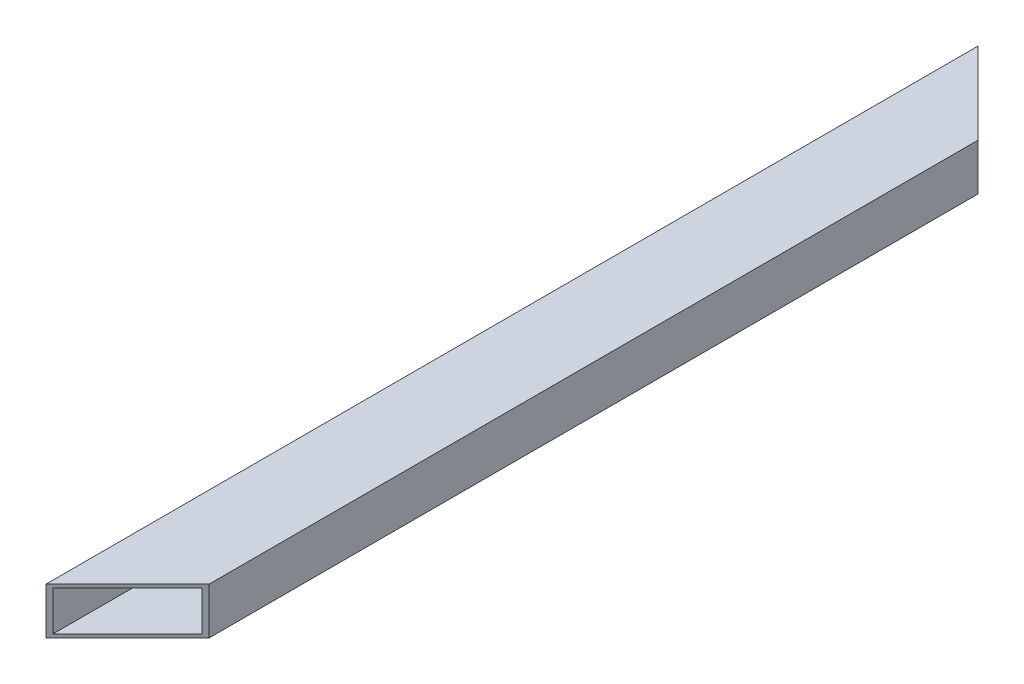
SolidWorks part; units mm, degrees
material "AISI 1020 Acier laminé à froid"
ref_plane "Plan de face" through (0, 0, 0) normal (0, 0, 1) x (1, 0, 0)
ref_plane "Plan de dessus" through (0, 0, 0) normal (0, 1, 0) x (1, 0, 0)
ref_plane "Plan de droite" through (0, 0, 0) normal (1, 0, 0) x (0, 0, -1)
sketch "Esquisse1" plane through (0, 0, 0) normal (0, 0, 1) x (1, 0, 0)
  line L1 (0, 0) -> (35, 0)
  line L2 (0, 0) -> (0, 20)
  line L3 (0, 20) -> (35, 20)
  line L4 (35, 0) -> (35, 20)
  line L5 (1.5, 18.5) -> (33.5, 18.5)
  line L6 (1.5, 18.5) -> (1.5, 1.5)
  line L7 (1.5, 1.5) -> (33.5, 1.5)
  line L8 (33.5, 18.5) -> (33.5, 1.5)
  dimension "D1" = 35
  dimension "D2" = 20
  dimension "D3" = 1.5
  dimension "D4" = 1.5
  dimension "D5" = 1.5
  dimension "D6" = 1.5
extrude "Boss.-Extru.1" add sketch "Esquisse1" along normal blind 400
sketch "Esquisse2" plane through (0, 0, 0) normal (0, 1, 0) x (1, 0, 0)
  line L0 (0, -400) -> (35, -365)
  line L1 (35, -400) -> (35, 0) construction
  line L2 (0, -400) -> (35, -400)
  line L3 (35, -400) -> (35, -365)
  dimension "D1" = 45
extrude "Enlèv. mat.-Extru.1" cut sketch "Esquisse2" along normal through all
sketch "Esquisse4" plane through (0, 0, 0) normal (0, 1, 0) x (1, 0, 0)
  line L0 (0, 0) -> (35, -35)
  line L1 (35, -365) -> (35, 0) construction
  line L2 (35, -35) -> (35, 0)
  line L3 (35, 0) -> (0, 0)
  dimension "D1" = 45
extrude "Enlèv. mat.-Extru.3" cut sketch "Esquisse4" along normal through all
